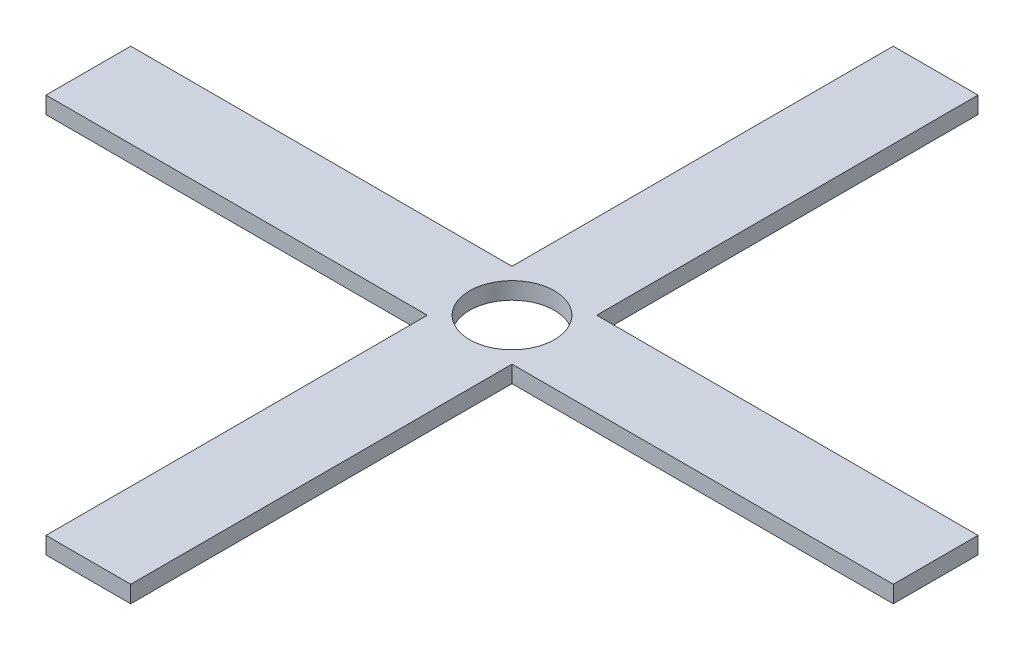
SolidWorks part; units mm, degrees
ref_plane "Front Plane" through (0, 0, 0) normal (0, 0, 1) x (1, 0, 0)
ref_plane "Top Plane" through (0, 0, 0) normal (0, 1, 0) x (1, 0, 0)
ref_plane "Right Plane" through (0, 0, 0) normal (1, 0, 0) x (0, 0, -1)
sketch "Sketch1" plane through (0, 0, 0) normal (0, 1, 0) x (1, 0, 0)
  line L1 (-2.5, -0.25) -> (2.5, -0.25)
  line L2 (-2.5, -0.25) -> (-2.5, 0.25)
  line L3 (-2.5, 0.25) -> (2.5, 0.25)
  line L4 (2.5, -0.25) -> (2.5, 0.25)
  line L5 (-2.5, -0.25) -> (2.5, 0.25) construction
  line L6 (-2.5, 0.25) -> (2.5, -0.25) construction
  point P0 (0, 0)
  dimension "D1" = 0.5
  dimension "D2" = 5
extrude "Boss-Extrude1" add sketch "Sketch1" along normal blind 0.1
sketch "Sketch2" plane through (0, 0, 0) normal (0, 1, 0) x (1, 0, 0)
  line L1 (-0.25, -2.5) -> (0.25, -2.5)
  line L2 (-0.25, -2.5) -> (-0.25, 2.5)
  line L3 (-0.25, 2.5) -> (0.25, 2.5)
  line L4 (0.25, -2.5) -> (0.25, 2.5)
  line L5 (-0.25, -2.5) -> (0.25, 2.5) construction
  line L6 (-0.25, 2.5) -> (0.25, -2.5) construction
  point P0 (0, 0)
  dimension "D1" = 5
  dimension "D2" = 0.5
extrude "Boss-Extrude2" add sketch "Sketch2" along normal blind 0.1
sketch "Sketch3" plane through (0, 0.1, 0) normal (0, 1, 0) x (1, 0, 0)
  circle A0 centre (0, 0) radius 0.25
  dimension "D1" = 0.5
extrude "Cut-Extrude1" cut sketch "Sketch3" against normal through all both and the other way through all
